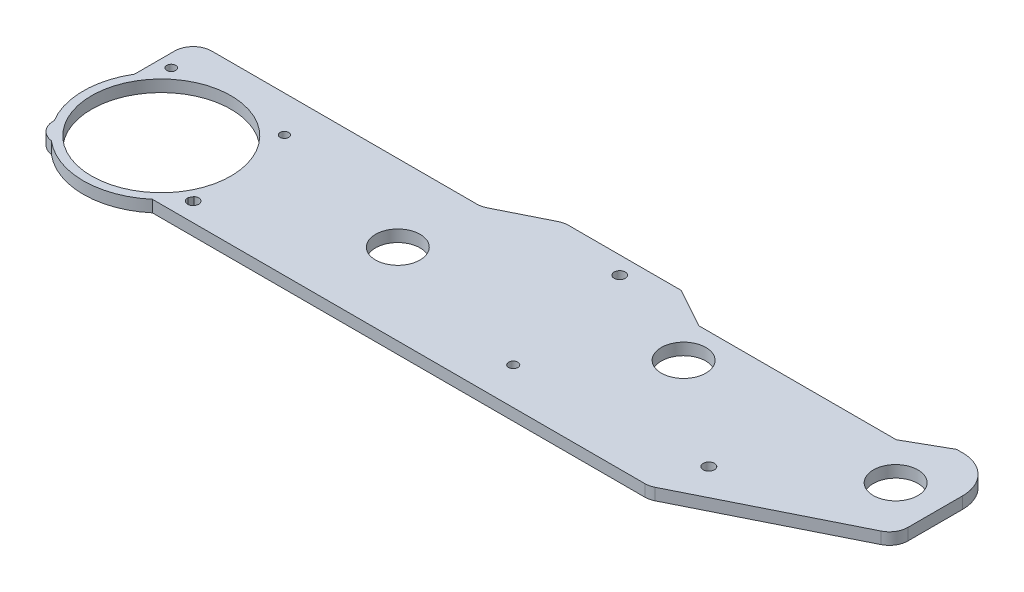
SolidWorks part; units mm, degrees
ref_plane "Front" through (0, 0, 0) normal (0, 0, 1) x (1, 0, 0)
ref_plane "Top" through (0, 0, 0) normal (0, 1, 0) x (1, 0, 0)
ref_plane "Right" through (0, 0, 0) normal (1, 0, 0) x (0, 0, -1)
sketch "Sketch1" plane through (0, 0, 0) normal (0, 1, 0) x (1, 0, 0)
  line L1 (0, 0) -> (210, 0)
  line L2 (0, 0) -> (0, -50)
  line L3 (0, -50) -> (210, -50)
  line L4 (210, 0) -> (210, -50)
  circle A7 centre (3.4895, -16.7877) radius 1.2117
  circle A8 centre (34.3726, -17.194) radius 1.1656
  circle A9 centre (37.5207, -44.9212) radius 1.5
  circle A10 centre (118.879, -40.0177) radius 1.25
  circle A11 centre (112.3021, -4.7393) radius 1.5
  circle A12 centre (168.9752, -37.4032) radius 1.5173
  dimension "D1" = 210
  dimension "D2" = 50
extrude "Boss-Extrude1" add sketch "Sketch1" along normal blind 3.175
sketch "Sketch2" plane through (0, 3.175, 0) normal (0, 1, 0) x (1, 0, 0)
  line L0 (210, 0) -> (0, 0) construction
  line L1 (0, 0) -> (0, -50) construction
  circle A0 centre (10, -26) radius 2
  circle A1 centre (10, -42) radius 2
  circle A2 centre (26, -26) radius 2
  circle A3 centre (26, -42) radius 2
  dimension "D1" = 16
  dimension "D2" = 16
  dimension "D3" = 16
  dimension "D4" = 26
  dimension "D5" = 10
  dimension "D6" = 10
  dimension "D7" = 26
  dimension "D8" = 16
extrude "Cut-Extrude1" cut sketch "Sketch2" against normal blind 10
sketch "Sketch3" plane through (0, 3.175, 0) normal (0, 1, 0) x (1, 0, 0)
  line L0 (210, 0) -> (0, 0) construction
  circle A0 centre (75.8499, -28.1) radius 6
  circle A1 centre (140.772, -16) radius 6
  circle A2 centre (18, -34) radius 0.587
  circle A3 centre (26, -26) radius 2 construction
  circle A4 centre (197.922, -16) radius 6
  dimension "D1" = 28.1
  dimension "D3" = 66.04
  dimension "D4" = 16
  dimension "D7" = 57.15
  dimension "D2" = 58.15
  dimension "D5" = 8
  dimension "D6" = 8
extrude "Cut-Extrude2" cut sketch "Sketch3" against normal blind 57.15
sketch "Sketch4" [suppressed] plane through (0, 3.175, 0) normal (0, 1, 0) x (1, 0, 0)
  line L0 (3.4895, -16.7877) -> (18, -34)
  line L1 (3.4895, -20.6627) -> (5.9498, -23.5811)
  line L2 (18, -34) -> (34.3726, -17.194)
  line L3 (34.3726, -17.194) -> (75.8499, -28.1)
  line L4 (75.8499, -28.1) -> (37.5207, -44.9212)
  line L5 (7.3432, -17.194) -> (9.8664, -20.303)
  circle A0 centre (18, -34) radius 15.9299
  circle A1 centre (3.4895, -16.7877) radius 3.8751
  circle A2 centre (34.3726, -17.194) radius 3.7227
  circle A3 centre (37.5207, -44.9212) radius 3.8676
  circle A4 centre (75.8499, -28.1) radius 12.797
  circle A5 centre (112.3021, -4.7393) radius 5.1588
  circle A6 centre (118.879, -40.0177) radius 4.9035
  circle A7 centre (140.772, -16) radius 12.6375
  circle A8 centre (168.9752, -37.4032) radius 4.2066
  circle A9 centre (197.922, -16) radius 12.8
sketch "Sketch5" [suppressed] plane through (0, 3.175, 0) normal (0, 1, 0) x (1, 0, 0)
  line L0 (210, 0) -> (0, 0) construction
  line L2 (-0.6266, -16.7877) -> (37.5207, -16.7877)
  line L3 (-0.6266, -16.7877) -> (-0.6266, -44.9212)
  line L4 (-0.6266, -44.9212) -> (37.5207, -44.9212)
  line L5 (37.5207, -16.7877) -> (37.5207, -44.9212)
  line L6 (75.8499, -15.182) -> (37.5207, -15.182)
  line L7 (75.8499, -15.182) -> (75.8499, -44.9212)
  line L8 (75.8499, -44.9212) -> (37.5207, -44.9212)
  line L9 (37.5207, -15.182) -> (37.5207, -44.9212)
  line L10 (112.3021, -4.7393) -> (75.8499, -4.7393)
  line L11 (112.3021, -4.7393) -> (112.3021, -44.9212)
  line L12 (112.3021, -44.9212) -> (75.8499, -44.9212)
  line L13 (75.8499, -4.7393) -> (75.8499, -44.9212)
  line L14 (112.3021, -4.7393) -> (102.3945, -4.7393)
  line L16 (112.3021, -4.7393) -> (112.3021, 0)
  line L17 (112.3021, 0) -> (102.3945, 0)
  line L18 (102.3945, -4.7393) -> (102.3945, 0)
  line L19 (210, -50) -> (210, 0) construction
  line L20 (112.3021, -4.7393) -> (123.1553, -4.7393)
  line L21 (112.3021, -4.7393) -> (112.3021, 0)
  line L22 (112.3021, 0) -> (123.1553, 0)
  line L23 (123.1553, -4.7393) -> (123.1553, 0)
  line L24 (112.3021, -4.7393) -> (140.772, -4.7393)
  line L25 (112.3021, -4.7393) -> (112.3021, -40.0177)
  line L26 (112.3021, -40.0177) -> (140.772, -40.0177)
  line L27 (140.772, -4.7393) -> (140.772, -40.0177)
  line L28 (140.772, -16) -> (168.9752, -16)
  line L29 (140.772, -16) -> (140.772, -40.0177)
  line L30 (140.772, -40.0177) -> (168.9752, -40.0177)
  line L31 (168.9752, -16) -> (168.9752, -40.0177)
  line L32 (168.9752, -4.7393) -> (210, -4.7393)
  line L33 (168.9752, -4.7393) -> (168.9752, -40.0177)
  line L34 (168.9752, -40.0177) -> (210, -40.0177)
  line L35 (210, -4.7393) -> (210, -40.0177)
  line L36 (0, -50) -> (210, -50) construction
  line L37 (160.7629, -40.0177) -> (177.2091, -40.0177)
  line L38 (160.7629, -40.0177) -> (160.7629, -44.9212)
  line L39 (160.7629, -44.9212) -> (177.2091, -44.9212)
  line L40 (177.2091, -40.0177) -> (177.2091, -44.9212)
  line L41 (112.3021, -40.0177) -> (126.3591, -40.0177)
  line L42 (112.3021, -40.0177) -> (112.3021, -47.7828)
  line L43 (112.3021, -47.7828) -> (126.3591, -47.7828)
  line L44 (126.3591, -40.0177) -> (126.3591, -47.7828)
  line L45 (30.5963, -44.9212) -> (44.6115, -44.9212)
  line L46 (30.5963, -44.9212) -> (30.5963, -50)
  line L47 (30.5963, -50) -> (44.6115, -50)
  line L48 (44.6115, -44.9212) -> (44.6115, -50)
  line L50 (-0.6266, -44.9212) -> (30.5963, -44.9212)
  line L51 (-0.6266, -44.9212) -> (-0.6266, -50)
  line L52 (-0.6266, -50) -> (30.5963, -50)
  line L53 (30.5963, -44.9212) -> (30.5963, -50)
  circle A0 centre (3.4895, -16.7877) radius 4.1161
  circle A1 centre (34.3726, -17.194) radius 3.8132
  circle A2 centre (75.8499, -28.1) radius 12.918
  circle A3 centre (112.3021, -4.7393) radius 5.2663
  circle A4 centre (140.772, -16) radius 13.0245
  circle A5 centre (197.922, -16) radius 12.3805
  circle A6 centre (168.9752, -37.4032) radius 4.7643
  circle A7 centre (118.879, -40.0177) radius 5.279
  circle A8 centre (37.5207, -44.9212) radius 4.2049
  line M12 (0, 0) -> (0, -50)
  line M13 (0, -50) -> (210, -50)
  line M14 (210, -50) -> (210, 0)
  line M15 (210, 0) -> (0, 0)
extrude "Cut-Extrude5" [suppressed] cut sketch "Sketch5" against normal blind 11.52 contours A5 L32 L23 L24 A4 L28 L33 M14 M15 | A1 L6 L13 L10 L18 A0 L2 M15 M12 | L8 L48 L34 L40 L39 L38 L30 L26 L44 L43 L42 L12 M13 M14
fillet "Fillet1" [suppressed] radius 5
sketch "Sketch10" plane through (0, 3.175, 0) normal (0, 1, 0) x (1, 0, 0)
  line L0 (210, -27.8594) -> (165.5029, -50)
  line L1 (210, -50) -> (210, 0) construction
  line L2 (0, -50) -> (210, -50) construction
  line L3 (165.5029, -50) -> (210, -50)
  line L4 (210, -50) -> (210, -27.8594)
  line L5 (92.5326, 0) -> (77.6548, -7.4028)
  line L6 (210, 0) -> (0, 0) construction
  line L7 (77.6548, -7.4028) -> (0, -7.4028)
  line L8 (0, 0) -> (0, -50) construction
  line L9 (0, -7.4028) -> (0, 0)
  line L10 (0, 0) -> (92.5326, 0)
  line L11 (124.11, 0) -> (134.7703, -5.8803)
  line L12 (134.7703, -5.8803) -> (187.9677, -5.8803)
  line L13 (187.9677, -5.8803) -> (198.3436, 0)
  line L14 (198.3436, 0) -> (124.11, 0)
extrude "Cut-Extrude7" cut sketch "Sketch10" against normal blind 10
fillet "Fillet3" radius 5 6 edges at (0, 1.5875, 50) (0, 1.5875, 7.4028) (77.6548, 1.5875, 7.4028) (92.5326, 1.5875, 0) (210, 1.5875, 27.8594) (165.5029, 1.5875, 50)
sketch "Sketch11" plane through (0, 3.175, 0) normal (0, 1, 0) x (1, 0, 0)
  circle A0 centre (18, -34) radius 21
  circle A1 centre (10, -26) radius 2
  circle A2 centre (10, -42) radius 2
  circle A3 centre (26, -26) radius 2
  circle A4 centre (26, -42) radius 2
extrude "Boss-Extrude4" add sketch "Sketch11" against normal blind 3.175
sketch "Sketch12" plane through (0, 3.175, 0) normal (0, 1, 0) x (1, 0, 0)
  circle A0 centre (18, -34) radius 18.78
extrude "Cut-Extrude8" cut sketch "Sketch12" against normal blind 10
fillet "Fillet4" radius 10 1 edges at (210, 1.5875, 0)
